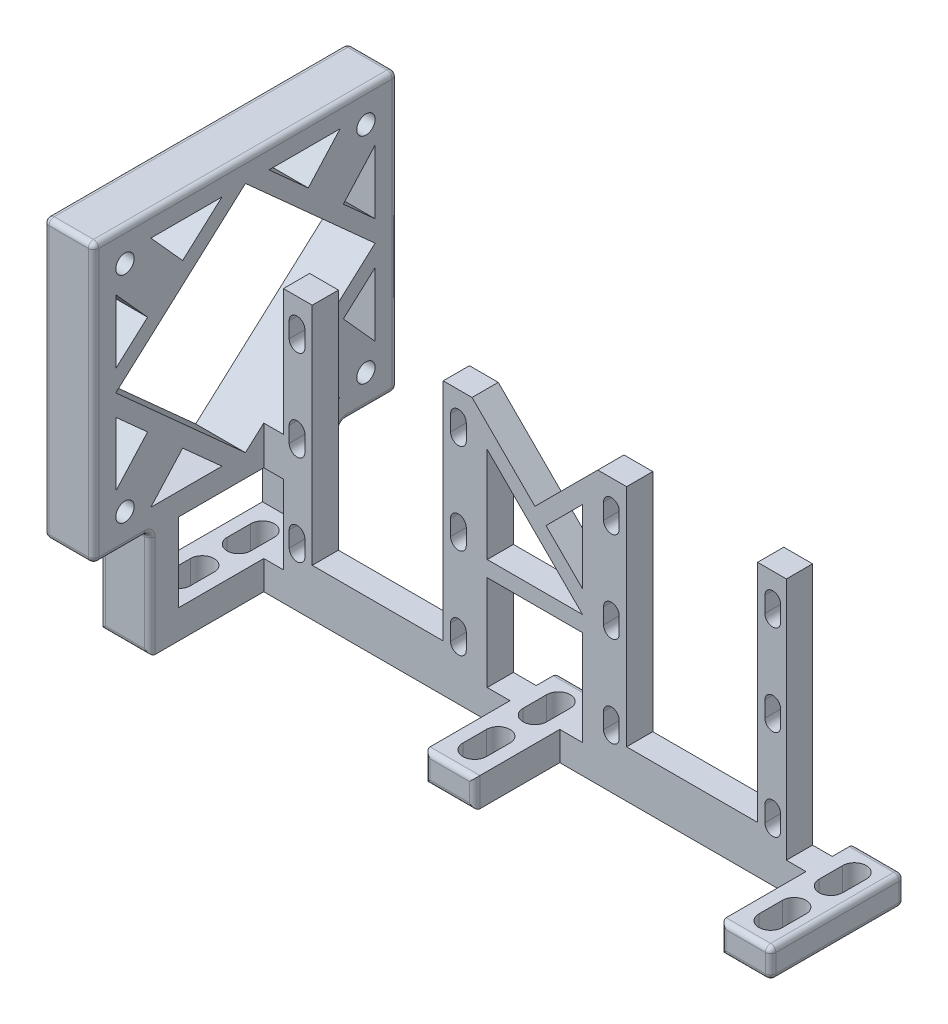
SolidWorks part; units mm, degrees
ref_plane "Plan de face" through (0, 0, 0) normal (0, 0, 1) x (1, 0, 0)
ref_plane "Plan de dessus" through (0, 0, 0) normal (0, 1, 0) x (1, 0, 0)
ref_plane "Plan de droite" through (0, 0, 0) normal (1, 0, 0) x (0, 0, -1)
sketch "Esquisse1" plane through (0, 0, 0) normal (0, 0, 1) x (1, 0, 0)
  line L0 (5.5, 52) -> (5.5, 9)
  line L1 (0, 0) -> (96, 0) construction
  line L2 (0, 0) -> (0, 52)
  line L3 (0, 52) -> (5.5, 52)
  line L4 (96, 0) -> (96, 52)
  line L5 (5.5, 9) -> (30.5, 9)
  line L6 (30.5, 9) -> (30.5, 52)
  line L7 (65.5, 52) -> (65.5, 9)
  line L8 (65.5, 9) -> (90.5, 9)
  line L9 (90.5, 9) -> (90.5, 52)
  line L10 (30.5, 52) -> (36, 52)
  line L11 (90.5, 52) -> (96, 52)
  line L12 (36, 52) -> (48, 40)
  line L13 (48, 40) -> (60, 52)
  line L14 (60, 52) -> (65.5, 52)
  line L15 (57.1, 5.5) -> (57.1, 0) construction
  line L16 (57.1, 5.5) -> (50.25, 5.5)
  line L17 (57.1, 5.5) -> (57.1, 23.6574)
  line L18 (57.1, 23.6574) -> (38.9, 23.6574)
  line L19 (38.9, 5.5) -> (38.9, 23.6574)
  line L20 (57.1, 44.8574) -> (50.1213, 37.8787)
  line L21 (50.1213, 37.8787) -> (57.1, 30.9)
  line L22 (57.1, 30.9) -> (57.1, 44.8574)
  line L23 (48, 0) -> (48, 40) construction
  line L24 (48, 40) -> (50.1213, 37.8787) construction
  line L25 (38.9, 44.8574) -> (57.1, 26.6574)
  line L26 (57.1, 26.6574) -> (38.9, 26.6574)
  line L27 (38.9, 26.6574) -> (38.9, 44.8574)
  line L28 (2.6, 12.65) -> (2.6, 9.65) construction
  line L29 (4.1, 12.65) -> (4.1, 9.65)
  line L30 (1.1, 12.65) -> (1.1, 9.65)
  line L31 (4.1, 11.15) -> (5.5, 11.15) construction
  line L32 (2.6, 29.95) -> (2.6, 26.95) construction
  line L33 (4.1, 29.95) -> (4.1, 26.95)
  line L34 (1.1, 29.95) -> (1.1, 26.95)
  line L35 (2.6, 47.25) -> (2.6, 44.25) construction
  line L36 (4.1, 47.25) -> (4.1, 44.25)
  line L37 (1.1, 47.25) -> (1.1, 44.25)
  line L38 (2.6, 26.95) -> (2.6, 12.65) construction
  line L39 (2.6, 29.95) -> (2.6, 44.25) construction
  line L40 (18, 9) -> (18, 52) construction
  line L41 (33.4, 47.25) -> (33.4, 44.25) construction
  line L42 (31.9, 47.25) -> (31.9, 44.25)
  line L43 (34.9, 47.25) -> (34.9, 44.25)
  line L44 (33.4, 29.95) -> (33.4, 26.95) construction
  line L45 (31.9, 29.95) -> (31.9, 26.95)
  line L46 (34.9, 29.95) -> (34.9, 26.95)
  line L47 (33.4, 12.65) -> (33.4, 9.65) construction
  line L48 (31.9, 12.65) -> (31.9, 9.65)
  line L49 (34.9, 12.65) -> (34.9, 9.65)
  line L50 (33.4, 29.95) -> (38.9, 29.95) construction
  line L51 (93.4, 12.65) -> (93.4, 9.65) construction
  line L52 (91.9, 12.65) -> (91.9, 9.65)
  line L53 (94.9, 12.65) -> (94.9, 9.65)
  line L54 (93.4, 29.95) -> (93.4, 26.95) construction
  line L55 (91.9, 29.95) -> (91.9, 26.95)
  line L56 (94.9, 29.95) -> (94.9, 26.95)
  line L57 (93.4, 47.25) -> (93.4, 44.25) construction
  line L58 (91.9, 47.25) -> (91.9, 44.25)
  line L59 (94.9, 47.25) -> (94.9, 44.25)
  line L60 (62.6, 47.25) -> (62.6, 44.25) construction
  line L61 (64.1, 47.25) -> (64.1, 44.25)
  line L62 (61.1, 47.25) -> (61.1, 44.25)
  line L63 (62.6, 29.95) -> (62.6, 26.95) construction
  line L64 (64.1, 29.95) -> (64.1, 26.95)
  line L65 (61.1, 29.95) -> (61.1, 26.95)
  line L66 (62.6, 12.65) -> (62.6, 9.65) construction
  line L67 (64.1, 12.65) -> (64.1, 9.65)
  line L68 (61.1, 12.65) -> (61.1, 9.65)
  line L69 (62.6, 29.95) -> (57.1, 29.95) construction
  line L70 (48, 40) -> (45.8787, 37.8787) construction
  line L71 (57.1, 26.6574) -> (57.1, 23.6574) construction
  line L72 (45.75, 5.5) -> (45.75, 0)
  line L73 (50.25, 0) -> (50.25, 5.5)
  line L74 (45.75, 5.5) -> (38.9, 5.5)
  line L75 (0, 0) -> (45.75, 0)
  line L76 (50.25, 0) -> (96, 0)
  line L77 (45.75, 5.5) -> (48, 5.5) construction
  line L78 (48, 5.5) -> (50.25, 5.5) construction
  circle A0 centre (2.6, 11.15) radius 1.5 construction
  circle A1 centre (2.6, 28.45) radius 1.5 construction
  circle A2 centre (2.6, 45.75) radius 1.5 construction
  arc A3 (4.1, 12.65) -> (1.1, 12.65) centre (2.6, 12.65) ccw
  arc A4 (1.1, 9.65) -> (4.1, 9.65) centre (2.6, 9.65) ccw
  arc A5 (4.1, 29.95) -> (1.1, 29.95) centre (2.6, 29.95) ccw
  arc A6 (1.1, 26.95) -> (4.1, 26.95) centre (2.6, 26.95) ccw
  arc A7 (4.1, 47.25) -> (1.1, 47.25) centre (2.6, 47.25) ccw
  arc A8 (1.1, 44.25) -> (4.1, 44.25) centre (2.6, 44.25) ccw
  arc A9 (31.9, 47.25) -> (34.9, 47.25) centre (33.4, 47.25) cw
  arc A10 (34.9, 44.25) -> (31.9, 44.25) centre (33.4, 44.25) cw
  arc A11 (31.9, 29.95) -> (34.9, 29.95) centre (33.4, 29.95) cw
  arc A12 (34.9, 26.95) -> (31.9, 26.95) centre (33.4, 26.95) cw
  arc A13 (31.9, 12.65) -> (34.9, 12.65) centre (33.4, 12.65) cw
  arc A14 (34.9, 9.65) -> (31.9, 9.65) centre (33.4, 9.65) cw
  arc A15 (91.9, 12.65) -> (94.9, 12.65) centre (93.4, 12.65) cw
  arc A16 (94.9, 9.65) -> (91.9, 9.65) centre (93.4, 9.65) cw
  arc A17 (91.9, 29.95) -> (94.9, 29.95) centre (93.4, 29.95) cw
  arc A18 (94.9, 26.95) -> (91.9, 26.95) centre (93.4, 26.95) cw
  arc A19 (91.9, 47.25) -> (94.9, 47.25) centre (93.4, 47.25) cw
  arc A20 (94.9, 44.25) -> (91.9, 44.25) centre (93.4, 44.25) cw
  arc A21 (64.1, 47.25) -> (61.1, 47.25) centre (62.6, 47.25) ccw
  arc A22 (61.1, 44.25) -> (64.1, 44.25) centre (62.6, 44.25) ccw
  arc A23 (64.1, 29.95) -> (61.1, 29.95) centre (62.6, 29.95) ccw
  arc A24 (61.1, 26.95) -> (64.1, 26.95) centre (62.6, 26.95) ccw
  arc A25 (64.1, 12.65) -> (61.1, 12.65) centre (62.6, 12.65) ccw
  arc A26 (61.1, 9.65) -> (64.1, 9.65) centre (62.6, 9.65) ccw
  point P37 (2.6, 11.15)
  point P44 (2.6, 28.45)
  point P51 (2.6, 45.75)
  point P67 (33.4, 45.75)
  point P74 (33.4, 28.45)
  point P81 (33.4, 11.15)
  point P86 (93.4, 11.15)
  point P95 (93.4, 28.45)
  point P102 (93.4, 45.75)
  point P109 (62.6, 45.75)
  point P116 (62.6, 28.45)
  point P123 (62.6, 11.15)
  dimension "D7" = 3
  dimension "D1" = 96
  dimension "D2" = 85
  dimension "D3" = 35
  dimension "D4" = 52
  dimension "D5" = 9
  dimension "D6" = 11.15
  dimension "D8" = 1.4
  dimension "D9" = 3
  dimension "D10" = 14.3
  dimension "D11" = 4.5
extrude "Boss.-Extru.1" add sketch "Esquisse1" along normal blind 5
sketch "Esquisse2" plane through (0, 0, 0) normal (0, -1, 0) x (1, 0, 0)
  line L0 (-3.75, -4.25) -> (43.25, -4.25) construction
  line L1 (-13.25, -4.25) -> (-3.75, -4.25)
  line L2 (-13.25, -4.25) -> (-13.25, 21.25)
  line L3 (-13.25, 21.25) -> (-3.75, 21.25)
  line L4 (-3.75, -4.25) -> (-3.75, 0)
  line L5 (43.25, 21.25) -> (52.75, 21.25)
  line L6 (43.25, 21.25) -> (43.25, -4.25)
  line L7 (43.25, -4.25) -> (52.75, -4.25)
  line L8 (52.75, 21.25) -> (52.75, -4.25)
  line L9 (109.25, 21.25) -> (99.75, 21.25)
  line L10 (109.25, 21.25) -> (109.25, -4.25)
  line L11 (109.25, -4.25) -> (99.75, -4.25)
  line L12 (99.75, 21.25) -> (99.75, 5)
  line L17 (52.75, -4.25) -> (99.75, -4.25) construction
  line L18 (-8.5, 0.5) -> (-8.5, 5) construction
  line L19 (-10.75, 0.5) -> (-10.75, 5)
  line L20 (-6.25, 0.5) -> (-6.25, 5)
  line L21 (-8.5, 12) -> (-8.5, 16.5) construction
  line L22 (-10.75, 12) -> (-10.75, 16.5)
  line L23 (-6.25, 12) -> (-6.25, 16.5)
  line L24 (-8.5, 18.75) -> (-8.5, 21.25) construction
  line L25 (-8.5, 9.75) -> (-8.5, 7.25) construction
  line L26 (-8.5, -1.75) -> (-8.5, -4.25) construction
  line L27 (-6.25, 14.25) -> (-3.75, 14.25) construction
  line L30 (19.75, -4.25) -> (19.75, 21.25) construction
  line L31 (48, 12) -> (48, 16.5) construction
  line L32 (50.25, 12) -> (50.25, 16.5)
  line L33 (45.75, 12) -> (45.75, 16.5)
  line L34 (48, 0.5) -> (48, 5) construction
  line L35 (50.25, 0.5) -> (50.25, 5)
  line L36 (45.75, 0.5) -> (45.75, 5)
  line L37 (76.25, -4.25) -> (76.25, 21.25) construction
  line L38 (104.5, 12) -> (104.5, 16.5) construction
  line L39 (102.25, 12) -> (102.25, 16.5)
  line L40 (106.75, 12) -> (106.75, 16.5)
  line L41 (104.5, 0.5) -> (104.5, 5) construction
  line L42 (102.25, 0.5) -> (102.25, 5)
  line L43 (106.75, 0.5) -> (106.75, 5)
  line L45 (0, 5) -> (-3.75, 5)
  line L46 (0, 5) -> (0, 0)
  line L47 (0, 0) -> (-3.75, 0)
  line L49 (96, 0) -> (99.75, 0)
  line L50 (96, 0) -> (96, 5)
  line L51 (96, 5) -> (99.75, 5)
  line L53 (-3.75, 5) -> (-3.75, 21.25)
  line L54 (99.75, 0) -> (99.75, -4.25)
  line L55 (45.75, 0) -> (50.25, 0) construction
  circle A0 centre (-8.5, 14.25) radius 2.25 construction
  circle A1 centre (-8.5, 2.75) radius 2.25 construction
  arc A2 (-10.75, 0.5) -> (-6.25, 0.5) centre (-8.5, 0.5) ccw
  arc A3 (-6.25, 5) -> (-10.75, 5) centre (-8.5, 5) ccw
  arc A4 (-10.75, 12) -> (-6.25, 12) centre (-8.5, 12) ccw
  arc A5 (-6.25, 16.5) -> (-10.75, 16.5) centre (-8.5, 16.5) ccw
  arc A6 (50.25, 12) -> (45.75, 12) centre (48, 12) cw
  arc A7 (45.75, 16.5) -> (50.25, 16.5) centre (48, 16.5) cw
  arc A8 (50.25, 0.5) -> (45.75, 0.5) centre (48, 0.5) cw
  arc A9 (45.75, 5) -> (50.25, 5) centre (48, 5) cw
  arc A10 (102.25, 12) -> (106.75, 12) centre (104.5, 12) ccw
  arc A11 (106.75, 16.5) -> (102.25, 16.5) centre (104.5, 16.5) ccw
  arc A12 (102.25, 0.5) -> (106.75, 0.5) centre (104.5, 0.5) ccw
  arc A13 (106.75, 5) -> (102.25, 5) centre (104.5, 5) ccw
  point P16 (-8.5, 21.25)
  point P19 (-8.5, 2.75)
  point P24 (-8.5, 14.25)
  point P39 (104.5, -4.25)
  point P50 (48, 14.25)
  point P57 (48, 2.75)
  point P66 (104.5, 14.25)
  point P73 (104.5, 2.75)
  point P86 (48, 0)
  dimension "D2" = 4.5
  dimension "D1" = 11.5
  dimension "D3" = 113
extrude "Boss.-Extru.2" add sketch "Esquisse2" against normal up to surface (5.5 mm away) up to face at (53.675, 5.5, 2.5)
sketch "Esquisse3" plane through (-3.75, 0, 0) normal (1, 0, 0) x (0, 0, -1)
  line L0 (-21.25, 5.5) -> (4.25, 5.5) construction
  line L1 (20.5, 20.5) -> (-37.5, 20.5) construction
  line L2 (20.5, 20.5) -> (20.5, 73.5)
  line L3 (20.5, 73.5) -> (-37.5, 73.5)
  line L4 (-37.5, 20.5) -> (-37.5, 73.5)
  line L5 (-31.5, 26.5) -> (-37.5, 26.5) construction
  line L6 (-31.5, 26.5) -> (-31.5, 20.5) construction
  line L7 (14.5, 73.5) -> (14.5, 67.5) construction
  line L8 (14.5, 67.5) -> (20.5, 67.5) construction
  line L13 (-8.5, 69.25) -> (-33.25, 47)
  line L14 (-33.25, 47) -> (-8.5, 24.75)
  line L15 (-8.5, 24.75) -> (16.25, 47)
  line L16 (16.25, 47) -> (-8.5, 69.25)
  line L17 (-33.25, 47) -> (-37.5, 47) construction
  line L18 (-8.5, 69.25) -> (-8.5, 73.5) construction
  line L19 (16.25, 47) -> (20.5, 47) construction
  line L20 (-8.5, 24.75) -> (-8.5, 20.5) construction
  line L21 (-12.9873, 69.25) -> (-26.557, 69.25)
  line L22 (-26.557, 69.25) -> (-20.4919, 62.5035)
  line L23 (-20.4919, 62.5035) -> (-12.9873, 69.25)
  line L24 (-33.25, 51.0341) -> (-27.1849, 56.4865)
  line L25 (-27.1849, 56.4865) -> (-33.25, 63.2331)
  line L26 (-33.25, 63.2331) -> (-33.25, 51.0341)
  line L27 (-4.0127, 69.25) -> (3.4919, 62.5035)
  line L28 (3.4919, 62.5035) -> (9.557, 69.25)
  line L29 (9.557, 69.25) -> (-4.0127, 69.25)
  line L30 (16.25, 63.2331) -> (9.557, 69.25) construction
  line L31 (16.25, 63.2331) -> (16.25, 51.0341)
  line L32 (16.25, 51.0341) -> (10.1849, 56.4865)
  line L33 (10.1849, 56.4865) -> (16.25, 63.2331)
  line L46 (-33.25, 63.2331) -> (-26.557, 69.25) construction
  line L47 (10.1849, 37.5135) -> (16.25, 30.7669)
  line L48 (16.25, 42.9659) -> (10.1849, 37.5135)
  line L49 (16.25, 30.7669) -> (16.25, 42.9659)
  line L50 (3.4919, 31.4965) -> (9.557, 24.75)
  line L51 (-4.0127, 24.75) -> (3.4919, 31.4965)
  line L52 (9.557, 24.75) -> (-4.0127, 24.75)
  line L53 (-26.557, 24.75) -> (-20.4919, 31.4965)
  line L54 (-12.9873, 24.75) -> (-26.557, 24.75)
  line L55 (-20.4919, 31.4965) -> (-12.9873, 24.75)
  line L56 (-27.1849, 37.5135) -> (-33.25, 30.7669)
  line L57 (-33.25, 42.9659) -> (-27.1849, 37.5135)
  line L58 (-33.25, 30.7669) -> (-33.25, 42.9659)
  line L59 (-21.25, 0) -> (-21.25, 20.5)
  line L60 (-21.25, 0) -> (-26.75, 0)
  line L61 (-26.75, 0) -> (-26.75, 20.5)
  line L62 (-37.5, 20.5) -> (-26.75, 20.5)
  line L63 (4.25, 20.5) -> (4.25, 0)
  line L64 (4.25, 0) -> (9.75, 0)
  line L65 (9.75, 0) -> (9.75, 20.5)
  line L66 (-21.25, 20.5) -> (4.25, 20.5)
  line L67 (9.75, 20.5) -> (20.5, 20.5)
  line L68 (-21.25, 5.5) -> (-21.25, 0) construction
  circle A0 centre (-31.5, 67.5) radius 1.75
  circle A1 centre (14.5, 67.5) radius 1.75
  circle A2 centre (14.5, 26.5) radius 1.75
  circle A3 centre (-31.5, 26.5) radius 1.75
  point P6 (-8.5, 5.5)
  point P7 (-8.5, 20.5)
  point P24 (-8.5, 73.5)
  point P25 (20.5, 47)
  point P35 (-31.5, 69.25)
  dimension "D4" = 3.5
  dimension "D1" = 58
  dimension "D2" = 53
  dimension "D3" = 15
  dimension "D5" = 41
  dimension "D6" = 3
  dimension "D7" = 3
  dimension "D8" = 9
  dimension "D9" = 3
  dimension "D10" = 3
  dimension "D11" = 9
extrude "Boss.-Extru.3" add sketch "Esquisse3" against normal up to surface (9.5 mm away) up to face at (-13.25, 2.75, 8.5)
fillet "Congé1" radius 1 40 edges at (-3.75, 20.5, -15.125) (-13.25, 20.5, -15.125) (-3.75, 20.5, 32.125) (-13.25, 20.5, 32.125) (-3.75, 47, -20.5) (-13.25, 47, -20.5) (-8.5, 20.5, -20.5) (-3.75, 73.5, 8.5) (-13.25, 73.5, 8.5) (-8.5, 73.5, -20.5) (-3.75, 47, 37.5) (-8.5, 20.5, 37.5) (-13.25, 47, 37.5) (-8.5, 73.5, 37.5) (-3.75, 10.25, -9.75) (-8.5, 20.5, -9.75) (-13.25, 10.25, -9.75) (-8.5, 0, -9.75) (-3.75, 10.25, 26.75) (-8.5, 0, 26.75) (-13.25, 10.25, 26.75) (-8.5, 20.5, 26.75) (43.25, 2.75, -4.25) (48, 5.5, -4.25) (48, 0, -4.25) (52.75, 2.75, -4.25) (52.75, 2.75, 21.25) (48, 5.5, 21.25) (48, 0, 21.25) (43.25, 2.75, 21.25) (99.75, 2.75, -4.25) (104.5, 5.5, -4.25) (104.5, 0, -4.25) (109.25, 2.75, -4.25) (109.25, 5.5, 8.5) (109.25, 0, 8.5) (109.25, 2.75, 21.25) (104.5, 5.5, 21.25) (104.5, 0, 21.25) (99.75, 2.75, 21.25)
sketch "Esquisse4" plane through (-3.75, 0, 0) normal (1, 0, 0) x (0, 0, -1)
  line L0 (0, 5.5) -> (0, 52) construction
  line L1 (-5, 5.5) -> (-5, 52) construction
  line L2 (-21.25, 20.5) -> (4.25, 20.5) construction
  line L3 (-4.0127, 24.75) -> (9.557, 24.75) construction
  line L4 (3.4919, 31.4965) -> (-4.0127, 24.75) construction
  line L5 (-8.5, 24.75) -> (16.25, 47) construction
  line L6 (0, 20.5) -> (0, 24.75)
  line L7 (-5, 20.5) -> (-5, 27.8965)
  line L8 (-5, 20.5) -> (0, 20.5)
  line L9 (-4.0127, 24.75) -> (0, 24.75)
  line L10 (0, 28.3574) -> (-4.0127, 24.75)
  line L11 (-5, 27.8965) -> (0, 32.3914)
  line L12 (0, 28.3574) -> (0, 32.3914)
extrude "Boss.-Extru.4" add sketch "Esquisse4" along normal up to next
